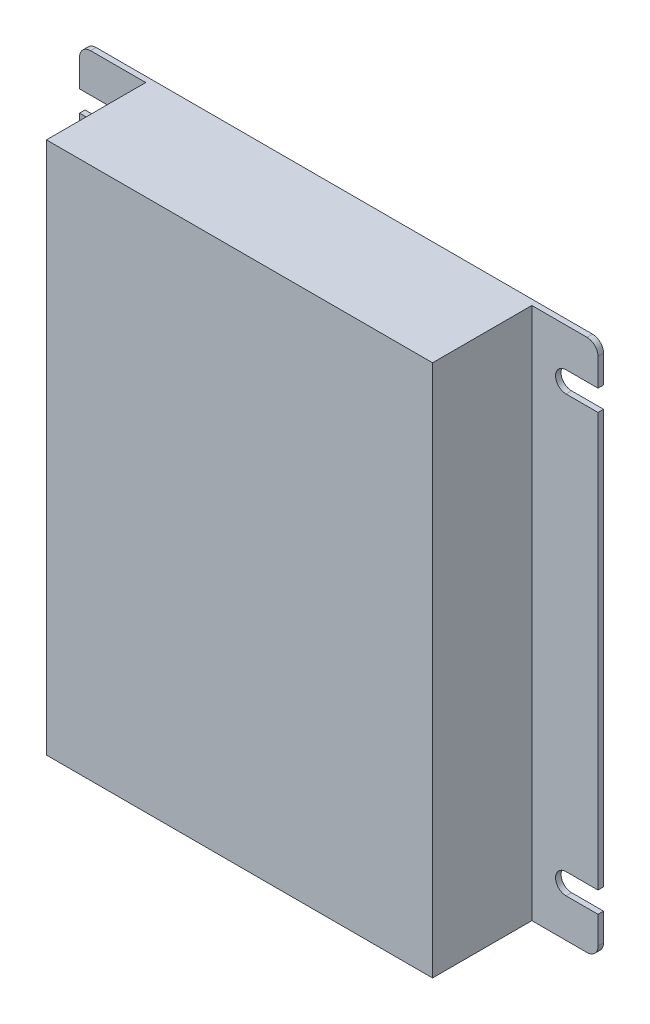
SolidWorks part; units mm, degrees
ref_plane "Front" through (0, 0, 0) normal (0, 0, 1) x (1, 0, 0)
ref_plane "Top" through (0, 0, 0) normal (0, 1, 0) x (1, 0, 0)
ref_plane "Right" through (0, 0, 0) normal (1, 0, 0) x (0, 0, -1)
sketch "Sketch1" plane through (0, 0, 0) normal (0, 0, 1) x (1, 0, 0)
  line L1 (-59.69, 61.341) -> (59.69, 61.341)
  line L2 (-59.69, 61.341) -> (-59.69, -61.341)
  line L3 (-59.69, -61.341) -> (59.69, -61.341)
  line L4 (59.69, 61.341) -> (59.69, -61.341)
  line L5 (-59.69, 61.341) -> (59.69, -61.341) construction
  line L6 (-59.69, -61.341) -> (59.69, 61.341) construction
  point P0 (0, 0)
  dimension "D1" = 119.38
  dimension "D2" = 122.682
extrude "Boss-Extrude1" add sketch "Sketch1" along normal blind 24.13
sketch "Sketch2" plane through (0, -61.341, 0) normal (0, -1, 0) x (1, 0, 0)
  line L0 (-59.69, 0) -> (59.69, 0) construction
  line L1 (59.69, 24.13) -> (44.45, 24.13)
  line L2 (59.69, 24.13) -> (59.69, 1.27)
  line L3 (59.69, 1.27) -> (44.45, 1.27)
  line L4 (44.45, 24.13) -> (44.45, 1.27)
  line L5 (-59.69, 24.13) -> (-44.45, 24.13)
  line L6 (-59.69, 24.13) -> (-59.69, 1.27)
  line L7 (-59.69, 1.27) -> (-44.45, 1.27)
  line L8 (-44.45, 24.13) -> (-44.45, 1.27)
  dimension "D1" = 1.27
  dimension "D2" = 15.24
extrude "Cut-Extrude1" cut sketch "Sketch2" against normal through all
sketch "Sketch3" plane through (0, 0, 1.27) normal (0, 0, 1) x (1, 0, 0)
  line L0 (-59.69, 50.038) -> (-52.324, 50.038) construction
  line L1 (-59.69, 61.341) -> (-59.69, -61.341) construction
  line L2 (-59.69, 52.451) -> (-52.324, 52.451)
  line L3 (-59.69, 47.625) -> (-52.324, 47.625)
  line L4 (-59.69, -50.038) -> (-52.324, -50.038) construction
  line L5 (-59.69, -47.625) -> (-52.324, -47.625)
  line L6 (-59.69, -52.451) -> (-52.324, -52.451)
  line L7 (59.69, -50.038) -> (52.324, -50.038) construction
  line L8 (59.69, 61.341) -> (59.69, -61.341) construction
  line L9 (59.69, -52.451) -> (52.324, -52.451)
  line L10 (59.69, -47.625) -> (52.324, -47.625)
  line L11 (59.69, 50.038) -> (52.324, 50.038) construction
  line L12 (59.69, 47.625) -> (52.324, 47.625)
  line L13 (59.69, 52.451) -> (52.324, 52.451)
  line L14 (-56.007, -50.038) -> (56.007, -50.038) construction
  line L15 (-56.007, 50.038) -> (56.007, 50.038) construction
  line L16 (0, 50.038) -> (0, 0) construction
  line L17 (0, 0) -> (0, -50.038) construction
  line L18 (-56.007, 50.038) -> (-56.007, -50.038) construction
  line L19 (56.007, 50.038) -> (56.007, -50.038) construction
  line L20 (44.45, -61.341) -> (59.69, -61.341) construction
  arc A0 (-59.69, 52.451) -> (-59.69, 47.625) centre (-59.69, 50.038) ccw
  arc A1 (-52.324, 47.625) -> (-52.324, 52.451) centre (-52.324, 50.038) ccw
  arc A2 (-59.69, -47.625) -> (-59.69, -52.451) centre (-59.69, -50.038) ccw
  arc A3 (-52.324, -52.451) -> (-52.324, -47.625) centre (-52.324, -50.038) ccw
  arc A4 (59.69, -52.451) -> (59.69, -47.625) centre (59.69, -50.038) ccw
  arc A5 (52.324, -47.625) -> (52.324, -52.451) centre (52.324, -50.038) ccw
  arc A6 (59.69, 47.625) -> (59.69, 52.451) centre (59.69, 50.038) ccw
  arc A7 (52.324, 52.451) -> (52.324, 47.625) centre (52.324, 50.038) ccw
  point P4 (-56.007, 50.038)
  point P11 (-56.007, -50.038)
  point P16 (56.007, -50.038)
  point P25 (56.007, 50.038)
  dimension "D1" = 4.826
  dimension "D2" = 7.366
  dimension "D3" = 8.89
extrude "Cut-Extrude2" cut sketch "Sketch3" against normal through all
fillet "Fillet1" radius 2.54 4 edges at (-59.69, 61.341, 0.635) (-59.69, -61.341, 0.635) (59.69, -61.341, 0.635) (59.69, 61.341, 0.635)
